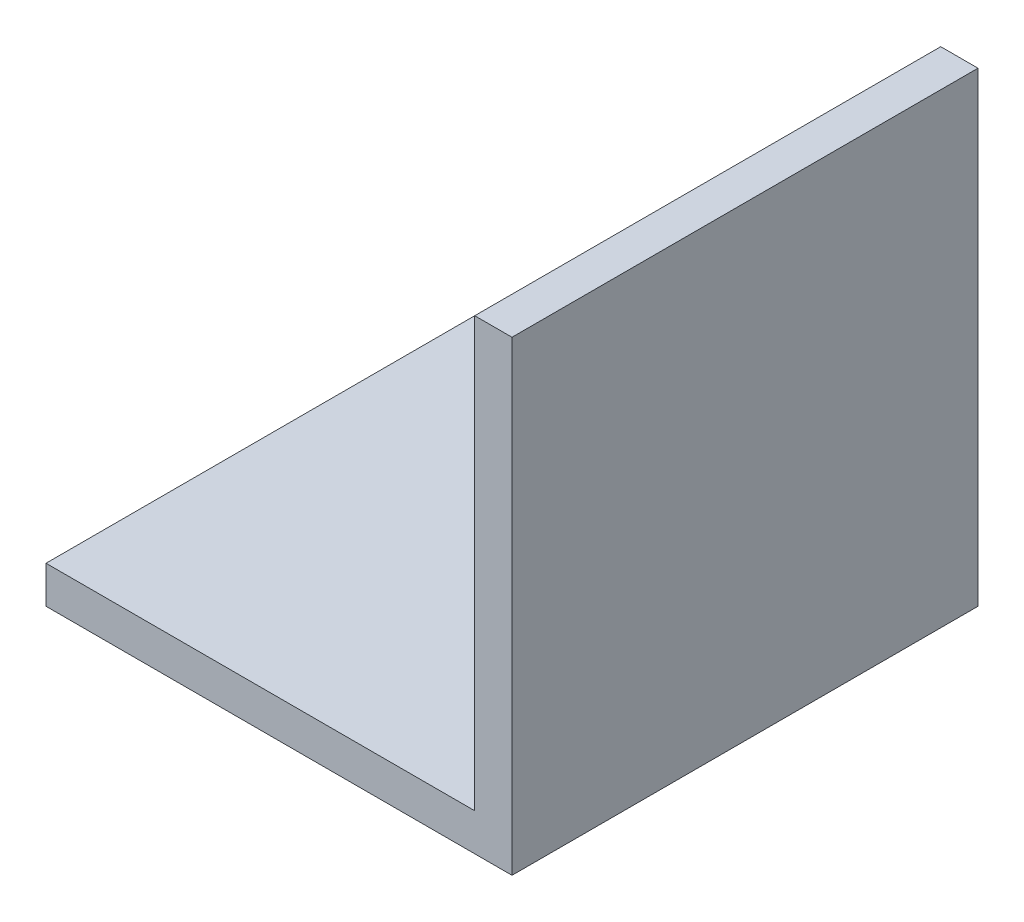
SolidWorks part; units mm, degrees
ref_plane "Front Plane" through (0, 0, 0) normal (0, 0, 1) x (1, 0, 0)
ref_plane "Top Plane" through (0, 0, 0) normal (0, 1, 0) x (1, 0, 0)
ref_plane "Right Plane" through (0, 0, 0) normal (1, 0, 0) x (0, 0, -1)
sketch "Sketch1" plane through (0, 0, 0) normal (0, 0, 1) x (1, 0, 0)
  line L0 (-34.4285, -7.3836) -> (15.5715, -7.3836)
  line L1 (-34.4285, -3.3836) -> (11.5715, -3.3836)
  line L2 (-34.4285, -3.3836) -> (-34.4285, -7.3836)
  line L6 (15.5715, -7.3836) -> (15.5715, 42.6164)
  line L7 (15.5715, 42.6164) -> (11.5715, 42.6164)
  line L8 (11.5715, -3.3836) -> (11.5715, 42.6164)
  dimension "D1" = 50
  dimension "D2" = 50
  dimension "D3" = 4
  dimension "D4" = 4
extrude "Boss-Extrude1" add sketch "Sketch1" along normal blind 50
